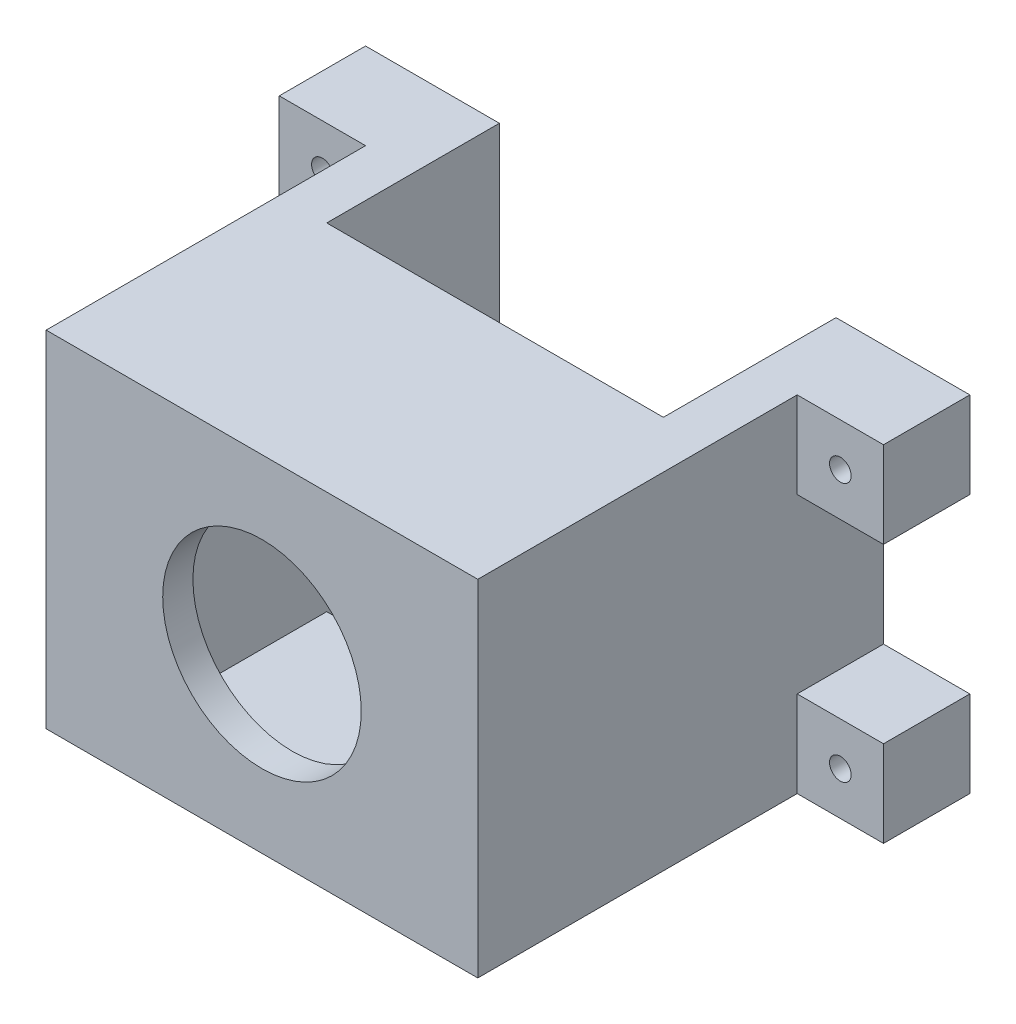
SolidWorks part; units mm, degrees
ref_plane "正面" through (0, 0, 0) normal (0, 0, 1) x (1, 0, 0)
ref_plane "平面" through (0, 0, 0) normal (0, 1, 0) x (1, 0, 0)
ref_plane "右側面" through (0, 0, 0) normal (1, 0, 0) x (0, 0, -1)
sketch "ｽｹｯﾁ1" plane through (0, 0, 0) normal (0, 0, 1) x (1, 0, 0)
  line L1 (-25, 20) -> (25, 20)
  line L2 (-25, 20) -> (-25, -20)
  line L3 (-25, -20) -> (25, -20)
  line L4 (25, 20) -> (25, -20)
  line L5 (-25, 20) -> (25, -20) construction
  line L6 (-25, -20) -> (25, 20) construction
  point P0 (0, 0)
  dimension "D1" = 40
  dimension "D2" = 50
extrude "ﾎﾞｽ - 押し出し2" add sketch "ｽｹｯﾁ1" along normal blind 47
sketch "ｽｹｯﾁ3" plane through (0, 0, 0) normal (0, 0, 1) x (1, 0, 0)
  line L0 (-25, -20) -> (25, -20) construction
  line L1 (-35, -10) -> (35, -10)
  line L2 (-35, -10) -> (-35, -20)
  line L3 (-35, -20) -> (35, -20)
  line L4 (35, -10) -> (35, -20)
  line L5 (-35, -10) -> (35, -20) construction
  line L6 (-35, -20) -> (35, -10) construction
  point P0 (0, -15)
  dimension "D1" = 70
  dimension "D2" = 0
  dimension "D3" = 10
  dimension "D4" = 0
extrude "ﾎﾞｽ - 押し出し3" add sketch "ｽｹｯﾁ3" along normal blind 10
sketch "ｽｹｯﾁ4" plane through (0, 0, 0) normal (0, 0, 1) x (1, 0, 0)
  circle A0 centre (0, 0) radius 11.5
  dimension "D1" = 23
extrude "ｶｯﾄ - 押し出し1" cut sketch "ｽｹｯﾁ4" along normal through all both and the other way through all contours A0
sketch "ｽｹｯﾁ5" plane through (0, 0, 0) normal (0, 0, 1) x (1, 0, 0)
  line L1 (-19.5, 19) -> (19.5, 19)
  line L2 (-19.5, 19) -> (-19.5, -19)
  line L3 (-19.5, -19) -> (19.5, -19)
  line L4 (19.5, 19) -> (19.5, -19)
  line L5 (-19.5, 19) -> (19.5, -19) construction
  line L6 (-19.5, -19) -> (19.5, 19) construction
  point P0 (0, 0)
  dimension "D1" = 39
  dimension "D2" = 38
extrude "ｶｯﾄ - 押し出し2" cut sketch "ｽｹｯﾁ5" along normal blind 43.5
hole_wizard "M3x0.5 ねじ穴1" positions "ｽｹｯﾁ6" profile "ｽｹｯﾁ7" tap size "M3x0.5" standard "JIS" end condition through all
sketch "ｽｹｯﾁ6" plane through (0, 0, 10) normal (0, 0, 1) x (1, 0, 0)
  point P0 (30, -15)
  point P2 (-30, -15)
  dimension "D1" = 30
  dimension "D2" = 30
  dimension "D3" = 15
  dimension "D4" = 15
sketch "ｽｹｯﾁ7" plane through (30, -15, 10) normal (1, 0, 0) x (0, -1, 0)
  line L0 (0, 0) -> (0, 10)
  line L1 (0, 10) -> (1.25, 10)
  line L2 (1.25, 10) -> (1.25, 0)
  line L5 (1.25, 0) -> (0, 0)
  line L11 (0, -6.35) -> (0, 107.95) construction
  dimension "次ｻｰﾌｪｽまでのねじ下穴ﾄﾞﾘﾙ直径" = 2.5
  dimension "次ｻｰﾌｪｽまでのねじ下穴ﾄﾞﾘﾙの深さ" = 10
cosmetic thread "穴のねじ山1" parameters "D2"=3
cosmetic thread "穴のねじ山2" parameters "D2"=3
sketch "ｽｹｯﾁ8" plane through (0, 0, 0) normal (0, 0, -1) x (-1, 0, 0)
  line L1 (-19.5, 35) -> (19.5, 35)
  line L2 (-19.5, 35) -> (-19.5, -35)
  line L3 (-19.5, -35) -> (19.5, -35)
  line L4 (19.5, 35) -> (19.5, -35)
  line L5 (-19.5, 35) -> (19.5, -35) construction
  line L6 (-19.5, -35) -> (19.5, 35) construction
  point P0 (0, 0)
  dimension "D1" = 39
  dimension "D2" = 70
extrude "ｶｯﾄ - 押し出し3" cut sketch "ｽｹｯﾁ8" against normal blind 20
mirror "ﾐﾗｰ4" about plane through (0, 0, 0) normal (0, 1, 0) of "ｶｯﾄ - 押し出し2", "ｶｯﾄ - 押し出し3", "M3x0.5 ねじ穴1", "ﾎﾞｽ - 押し出し3"
cosmetic thread "穴のねじ山7" parameters "D2"=3
cosmetic thread "穴のねじ山8" parameters "D2"=3
